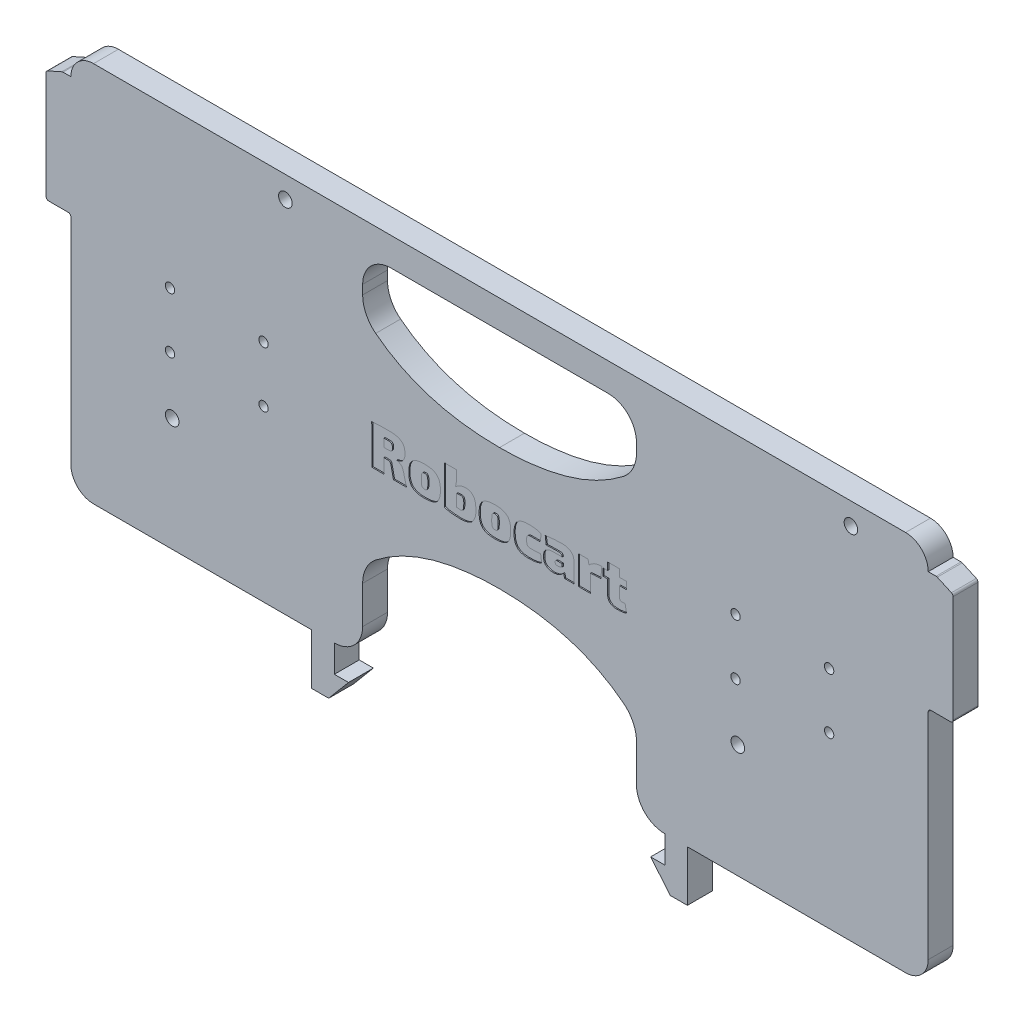
SolidWorks part; units mm, degrees
ref_plane "Front Plane" through (0, 0, 0) normal (0, 0, 1) x (1, 0, 0)
ref_plane "Top Plane" through (0, 0, 0) normal (0, 1, 0) x (1, 0, 0)
ref_plane "Right Plane" through (0, 0, 0) normal (1, 0, 0) x (0, 0, -1)
sketch "Sketch1" plane through (0, 0, 0) normal (0, 0, 1) x (1, 0, 0)
  line L0 (-35.4876, 0) -> (35.4876, 0) construction
  line L1 (0, 13.7325) -> (0, 0) construction
  line L2 (-96.2376, 42.8) -> (-30.7376, 42.8)
  line L3 (-96.2376, -42.8) -> (-96.2376, 42.8)
  line L4 (-96.2376, -42.8) -> (-30.7376, -42.8)
  line L5 (-30.7376, 42.8) -> (-30.7376, 24.5941)
  line L6 (30.7376, 42.8) -> (96.2376, 42.8)
  line L7 (30.7376, 42.8) -> (30.7376, 24.5941)
  line L8 (30.7376, -42.8) -> (96.2376, -42.8)
  line L9 (96.2376, -42.8) -> (96.2376, 42.8)
  line L10 (15.7308, 13.7325) -> (-15.7308, 13.7325) construction
  line L11 (-30.7376, -24.5941) -> (-30.7376, -42.8)
  line L12 (30.7376, -24.5941) -> (30.7376, -42.8)
  spline S0 degree 2 poles (-30.7376, 24.5941) (-19.6635, 13.7325) (0, 13.7325) knots 0 0 0 1 1 1
  spline S1 degree 2 poles (30.7376, 24.5941) (19.6635, 13.7325) (0, 13.7325) knots 0 0 0 1 1 1
  spline S2 degree 2 poles (30.7376, -24.5941) (19.6635, -13.7325) (0, -13.7325) knots 0 0 0 1 1 1
  spline S3 degree 2 poles (-30.7376, -24.5941) (-19.6635, -13.7325) (0, -13.7325) knots 0 0 0 1 1 1
  point P20 (-63.4876, -42.8)
  point P21 (63.4876, -42.8)
  line B0 (-91.4875, -42.8) -> (-35.4876, -42.8) construction
  line B1 (-35.4876, -42.8) -> (-35.4876, 42.8) construction
  line B2 (-35.4876, 42.8) -> (-91.4875, 42.8) construction
  line B3 (-91.4875, 42.8) -> (-91.4875, -42.8) construction
  circle B4 centre (-73.9876, 7.775) radius 1.05
  circle B5 centre (-73.9876, -4.725) radius 1.05
  circle B6 centre (-73.4874, -17.3) radius 1.524
  circle B7 centre (-52.9876, -4.725) radius 1.05
  circle B8 centre (-52.9876, 7.775) radius 1.05
  circle B9 centre (-48.0874, 37.9) radius 1.524
  line B10 (-63.4876, 1.525) -> (-63.4876, 42.8) construction
  circle B11 centre (52.9876, 7.775) radius 1.05
  circle B12 centre (52.9876, -4.725) radius 1.05
  circle B13 centre (53.4877, -17.3) radius 1.524
  circle B14 centre (73.9876, -4.725) radius 1.05
  circle B15 centre (73.9876, 7.775) radius 1.05
  circle B16 centre (78.8877, 37.9) radius 1.524
  dimension "D1" = 85.6
  dimension "D2" = 65.5
  dimension "D3" = 61.4751
sketch_block_instance "Block1-1"
sketch_block "Block1" parameters "D1"=2.5, "D3"=3.048, "D2"=21, "D4"=32.8, "D5"=32.8, "D6"=12.5, "D7"=39.05
sketch_block_instance "Block1-3"
extrude "Boss-Extrude1" add sketch "Sketch1" along normal blind 5.588
sketch "Sketch9" plane through (0, 0, 5.588) normal (0, 0, 1) x (1, 0, 0)
  line L0 (0, -42.8) -> (0, 13.08) construction
  line L1 (-25.4, 13.08) -> (25.4, 13.08) construction
  line L2 (-30.7376, -42.8) -> (30.7376, -42.8) construction
  circle A0 centre (-25.4, 13.08) radius 2.5273
  circle A1 centre (25.4, 13.08) radius 2.5273
  dimension "D1" = 5.0546
  dimension "D2" = 50.8
  dimension "D3" = 55.88
extrude "Cut-Extrude5" [suppressed] cut sketch "Sketch9" against normal through all
sketch "Sketch2" plane through (0, 0, 5.588) normal (0, 0, 1) x (1, 0, 0)
  line L0 (-29.4109, -4.4297) -> (29.4109, -4.4297) construction
  line L1 (0, 0) -> (0, -4.4297) construction
  text T0 "Robocart" font "Exo 2.0 Black" height in points 36
  dimension "D1" = 58.8219
extrude "Cut-Extrude1" cut sketch "Sketch2" against normal blind 0.254
sketch "Sketch3" plane through (0, 0, 0) normal (0, 0, 1) x (1, 0, 0)
  line L0 (30.7376, 42.8) -> (30.7376, 24.5941) construction
  line L1 (-30.7376, 42.8) -> (30.7376, 42.8)
  line L2 (-30.7376, 42.8) -> (-30.7376, 36.45)
  line L3 (-30.7376, 36.45) -> (30.7376, 36.45)
  line L4 (30.7376, 42.8) -> (30.7376, 36.45)
  dimension "D1" = 6.35
extrude "Boss-Extrude2" add sketch "Sketch3" along normal up to surface (5.588 mm away) up to face at (26.065, -0.1128, 5.588)
fillet "Fillet1" radius 5.08 4 edges at (96.2376, -42.8, 2.794) (96.2376, 42.8, 2.794) (-96.2376, -42.8, 2.794) (-96.2376, 42.8, 2.794)
fillet "Fillet2" radius 6.35 4 edges at (30.7376, -42.8, 2.794) (-30.7376, -42.8, 2.794) (30.7376, 36.45, 2.794) (-30.7376, 36.45, 2.794)
fillet "Fillet3" radius 7.62 4 edges at (30.7376, 24.5941, 2.794) (30.7376, -24.5941, 2.794) (-30.7376, -24.5941, 2.794) (-30.7376, 24.5941, 2.794)
sketch "Sketch4" plane through (0, 0, 0) normal (0, 0, 1) x (1, 0, 0)
  line L0 (-101.8256, 11.05) -> (-101.8256, 36.0676)
  line L1 (91.1576, 42.8) -> (-91.1576, 42.8) construction
  line L2 (-96.2376, 37.72) -> (-98.1426, 37.72)
  line L3 (-98.1426, 37.72) -> (-101.8256, 36.0676)
  line L4 (-96.2376, 37.72) -> (-96.2376, 11.05)
  line L5 (-101.8256, 11.05) -> (-96.2376, 11.05)
  line L6 (-96.2376, 37.72) -> (-96.2376, -37.72) construction
  line L7 (101.8256, 11.05) -> (96.2376, 11.05)
  line L8 (96.2376, 37.72) -> (96.2376, 11.05)
  line L9 (0, 36.45) -> (0, 0) construction
  line L10 (-24.3876, 36.45) -> (24.3876, 36.45) construction
  line L11 (98.1426, 37.72) -> (101.8256, 36.0676)
  line L12 (96.2376, 37.72) -> (98.1426, 37.72)
  line L13 (101.8256, 11.05) -> (101.8256, 36.0676)
  dimension "D1" = 31.75
  dimension "D2" = 5.588
  dimension "D3" = 24.163
  dimension "D4" = 1.905
  dimension ".25" = 5.08
extrude "Boss-Extrude3" add sketch "Sketch4" along normal up to surface (5.588 mm away) up to face at (-1.6357, -16.1355, 5.588)
fillet "Fillet4" radius 0.635 8 edges at (101.8256, 36.0676, 2.794) (-101.8256, 36.0676, 2.794) (-98.1426, 37.72, 2.794) (98.1426, 37.72, 2.794) (101.8256, 11.05, 2.794) (-101.8256, 11.05, 2.794) (96.2376, 11.05, 2.794) (-96.2376, 11.05, 2.794)
sketch "Sketch10" plane through (0, 0, 5.588) normal (0, 0, 1) x (1, 0, 0)
  line L0 (-37.0876, -42.8) -> (-37.0876, -48.896)
  line L1 (-37.0876, -48.896) -> (-33.9126, -48.896)
  line L2 (-33.9126, -48.896) -> (-38.3576, -54.1934)
  line L3 (-38.3576, -54.1934) -> (-42.1676, -54.1934)
  line L4 (-42.1676, -54.1934) -> (-42.1676, -42.8)
  line L5 (-91.1576, -42.8) -> (-37.0876, -42.8) construction
  line L6 (-42.1676, -42.8) -> (-37.0876, -42.8)
  line L7 (0, 0) -> (0, -37.8618) construction
  line L8 (42.1676, -42.8) -> (37.0876, -42.8)
  line L9 (42.1676, -54.1934) -> (42.1676, -42.8)
  line L10 (38.3576, -54.1934) -> (42.1676, -54.1934)
  line L11 (33.9126, -48.896) -> (38.3576, -54.1934)
  line L12 (37.0876, -48.896) -> (33.9126, -48.896)
  line L13 (37.0876, -42.8) -> (37.0876, -48.896)
  dimension "D1" = 5.08
  dimension "D2" = 3.81
  dimension "D3" = 3.175
  dimension "D4" = 6.096
  dimension "D5" = 50
extrude "Boss-Extrude4" add sketch "Sketch10" against normal up to surface (5.588 mm away) up to face at (3.0896, 27.656, 0)
